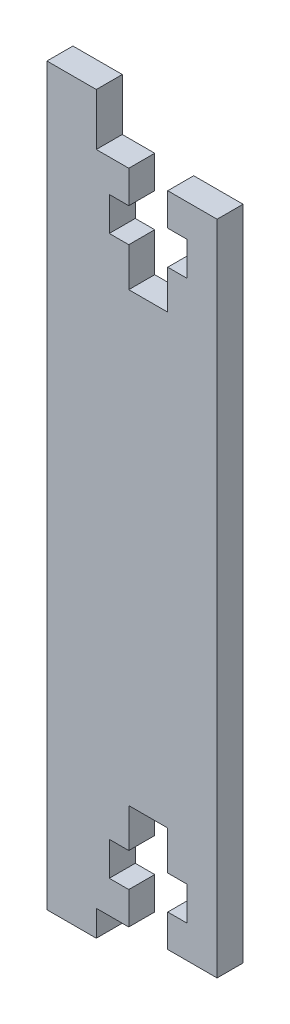
SolidWorks part; units mm, degrees
ref_plane "前视基准面" through (0, 0, 0) normal (0, 0, 1) x (1, 0, 0)
ref_plane "上视基准面" through (0, 0, 0) normal (0, 1, 0) x (1, 0, 0)
ref_plane "右视基准面" through (0, 0, 0) normal (1, 0, 0) x (0, 0, -1)
sketch "草图1" plane through (0, 0, 0) normal (0, 0, 1) x (1, 0, 0)
  line L0 (-4.0171, 28.4457) -> (-7.8171, 28.4457)
  line L1 (-4.0171, 24.4457) -> (-1.5171, 24.4457)
  line L2 (1.4829, 24.4457) -> (5.2829, 24.4457)
  line L3 (-4.0171, 28.4457) -> (-4.0171, 24.4457)
  line L4 (-3.0171, 21.9457) -> (-3.0171, 19.3457)
  line L5 (-3.0171, 19.3457) -> (-1.5171, 19.3457)
  line L6 (-1.5171, 19.3457) -> (-1.5171, 16.3457)
  line L7 (1.4829, 19.3457) -> (1.4829, 16.3457)
  line L8 (2.9829, 19.3457) -> (1.4829, 19.3457)
  line L9 (2.9829, 21.9457) -> (2.9829, 19.3457)
  line L10 (-1.5171, 21.9457) -> (-3.0171, 21.9457)
  line L11 (-1.5171, 16.3457) -> (1.4829, 16.3457)
  line L12 (1.4829, 21.9457) -> (2.9829, 21.9457)
  line L13 (-1.5171, 21.9457) -> (-1.5171, 24.4457)
  line L14 (1.4829, 21.9457) -> (1.4829, 24.4457)
  line L15 (-7.8171, -28.1543) -> (-7.8171, -26.1543)
  line L16 (5.2829, -26.1543) -> (1.4829, -26.1543)
  line L17 (-1.5171, -23.6543) -> (-1.5171, -26.1543)
  line L18 (1.4829, -26.1543) -> (1.4829, -23.6543)
  line L19 (-1.5171, -18.0543) -> (1.4829, -18.0543)
  line L20 (-1.5171, -23.6543) -> (-3.0171, -23.6543)
  line L21 (1.4829, -23.6543) -> (2.9829, -23.6543)
  line L22 (2.9829, -23.6543) -> (2.9829, -21.0543)
  line L23 (1.4829, -21.0543) -> (1.4829, -18.0543)
  line L24 (-1.5171, -21.0543) -> (-1.5171, -18.0543)
  line L25 (-3.0171, -21.0543) -> (-1.5171, -21.0543)
  line L26 (-3.0171, -23.6543) -> (-3.0171, -21.0543)
  line L27 (-4.0171, -28.1543) -> (-4.0171, -26.1543)
  line L28 (2.9829, -21.0543) -> (1.4829, -21.0543)
  line L29 (-4.0171, -26.1543) -> (-1.5171, -26.1543)
  line L30 (-7.8171, 28.4457) -> (-7.8171, 24.4457)
  line L31 (-4.0171, -28.1543) -> (-7.8171, -28.1543)
  line L32 (5.2829, -26.1543) -> (5.2829, 24.4457)
  line L33 (-1.5171, -18.0543) -> (-1.5171, 16.3457) construction
  line L34 (-7.8171, -26.1543) -> (-7.8171, 24.4457)
  point P0 (-1.5171, 23.1957)
  dimension "D1" = 3.8
  dimension "D2" = 3
  dimension "D3" = 2.5
  dimension "D4" = 1.5
  dimension "D5" = 2.6
  dimension "D6" = 1.5
  dimension "D7" = 3
  dimension "D8" = 3
  dimension "D9" = 3
  dimension "D10" = 2.6
  dimension "D11" = 1.5
  dimension "D12" = 2.5
  dimension "D13" = 3.8
  dimension "D14" = 4
extrude "凸台-拉伸1" add sketch "草图1" along normal blind 2 contours L34 L30 L0 L3 L1 L13 L10 L4 L5 L6 L11 L7 L8 L9 L12 L14 L2 L32 L16 L18 L21 L22 L28 L23 L19 L24 L25 L26 L20 L17 L29 L27 L31 L15
sketch "草图2" plane through (0, -26.1543, 0) normal (0, -1, 0) x (1, 0, 0)
  line L0 (-1.5171, 1) -> (1.4829, 1) construction
  line L1 (-1.5171, 2) -> (-1.5171, 0) construction
  line L2 (1.4829, 2) -> (1.4829, 0) construction
  circle A0 centre (-0.0171, 1) radius 1.5
